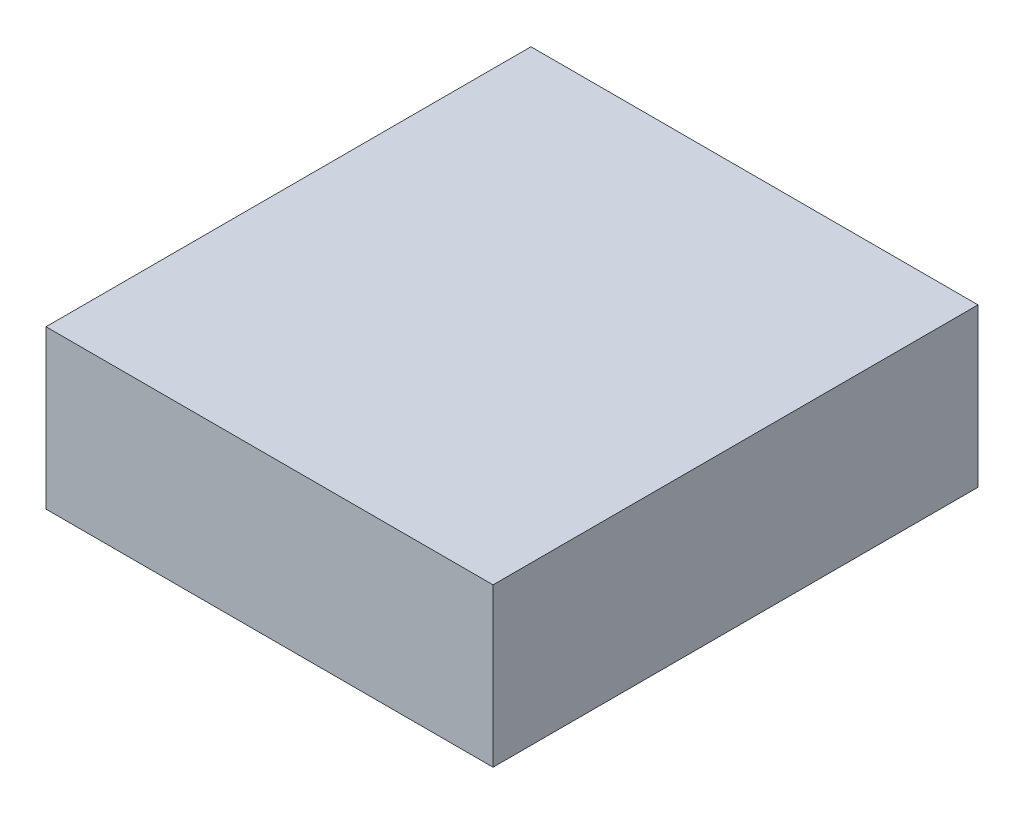
SolidWorks part; units mm, degrees
material "AISI 1020"
ref_plane "Front Plane" through (0, 0, 0) normal (0, 0, 1) x (1, 0, 0)
ref_plane "Top Plane" through (0, 0, 0) normal (0, 1, 0) x (1, 0, 0)
ref_plane "Right Plane" through (0, 0, 0) normal (1, 0, 0) x (0, 0, -1)
sketch "Sketch1" plane through (0, 0, 0) normal (0, 1, 0) x (1, 0, 0)
  line L1 (-42.4469, -46.0462) -> (42.4469, -46.0462)
  line L2 (-42.4469, -46.0462) -> (-42.4469, 46.0462)
  line L3 (-42.4469, 46.0462) -> (42.4469, 46.0462)
  line L4 (42.4469, -46.0462) -> (42.4469, 46.0462)
  line L5 (-42.4469, -46.0462) -> (42.4469, 46.0462) construction
  line L6 (-42.4469, 46.0462) -> (42.4469, -46.0462) construction
  point P0 (0, 0)
extrude "Boss-Extrude1" add sketch "Sketch1" along normal blind 30
